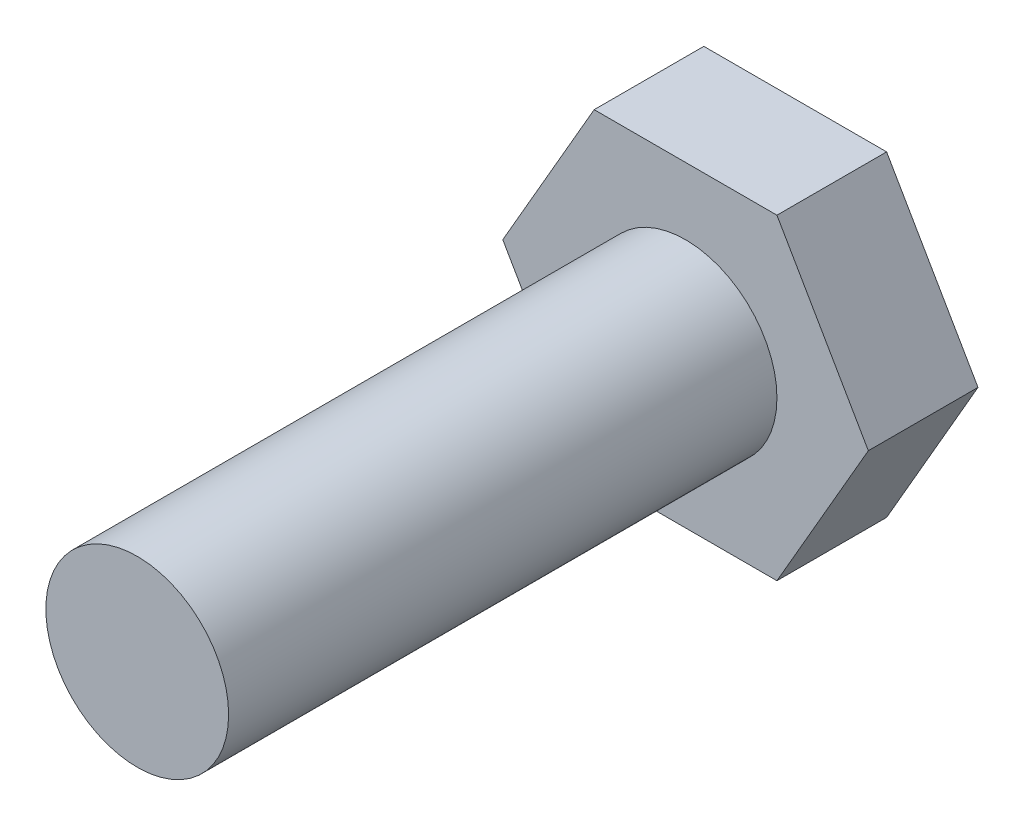
SolidWorks part; units mm, degrees
ref_plane "前视基准面" through (0, 0, 0) normal (0, 0, 1) x (1, 0, 0)
ref_plane "上视基准面" through (0, 0, 0) normal (0, 1, 0) x (1, 0, 0)
ref_plane "右视基准面" through (0, 0, 0) normal (1, 0, 0) x (0, 0, -1)
other "Configuration Table"
sketch "草图1" plane through (0, 0, 0) normal (0, 0, 1) x (1, 0, 0)
  line L1 (10, 0) -> (5, 8.6603)
  line L2 (5, 8.6603) -> (-5, 8.6603)
  line L3 (-5, 8.6603) -> (-10, 0)
  line L4 (-10, 0) -> (-5, -8.6603)
  line L5 (-5, -8.6603) -> (5, -8.6603)
  line L6 (5, -8.6603) -> (10, 0)
  circle A0 centre (0, 0) radius 8.6603 construction
extrude "凸台-拉伸1" add sketch "草图1" along normal blind 6
sketch "草图2" plane through (0, 0, 6) normal (0, 0, 1) x (1, 0, 0)
  circle A0 centre (0, 0) radius 5
extrude "凸台-拉伸2" add sketch "草图2" along normal blind 30
